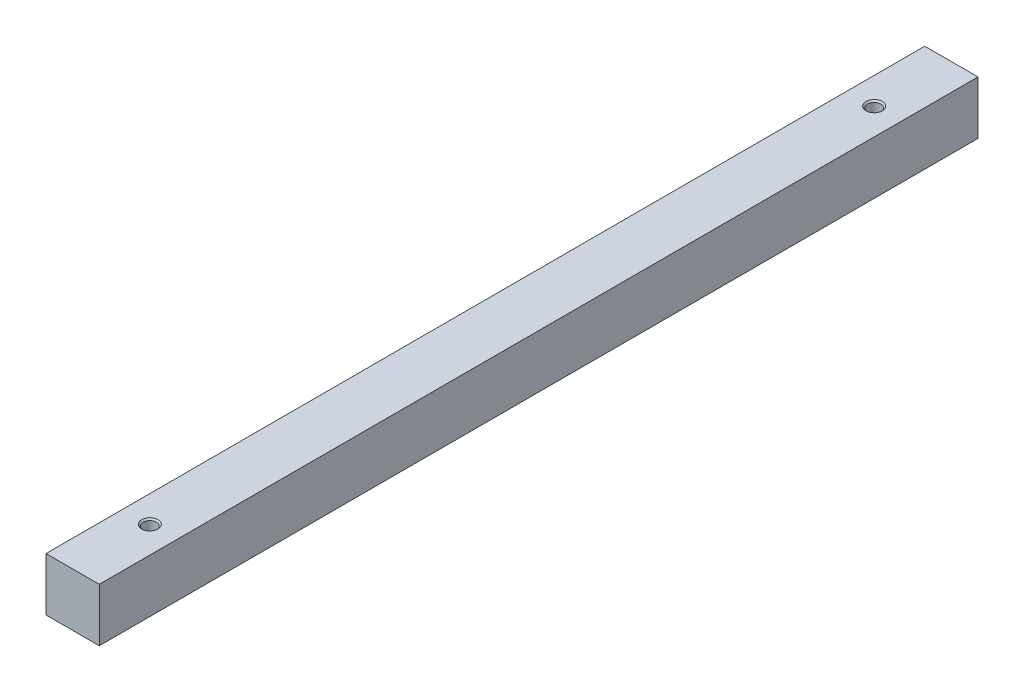
SolidWorks part; units mm, degrees
ref_plane "Plan de face" through (0, 0, 0) normal (0, 0, 1) x (1, 0, 0)
ref_plane "Plan de dessus" through (0, 0, 0) normal (0, 1, 0) x (1, 0, 0)
ref_plane "Plan de droite" through (0, 0, 0) normal (1, 0, 0) x (0, 0, -1)
sketch "Esquisse1" plane through (0, 0, 0) normal (0, 0, 1) x (1, 0, 0)
  line L0 (-5, 5) -> (5, -5) construction
  line L1 (-5, 5) -> (5, 5)
  line L2 (-5, 5) -> (-5, -5)
  line L3 (-5, -5) -> (5, -5)
  line L4 (5, 5) -> (5, -5)
  dimension "D1" = 10
extrude "Boss.-Extru.1" add sketch "Esquisse1" along normal mid plane 165
hole_wizard "Trou taraudé M3x0.52" positions "Esquisse5" profile "Esquisse4" tap size "M3x0.5" standard "Ansi Metric" end condition through all
sketch "Esquisse5" plane through (0, 5, 0) normal (0, 1, 0) x (1, 0, 0)
  line L0 (0, 0) -> (-36.1539, 0) construction
  line L2 (5, 82.5) -> (-5, 82.5) construction
  point P0 (0, 68)
  point P2 (0, -68)
  dimension "D1" = 68
  dimension "D2" = 14.5
sketch "Esquisse4" plane through (0, 5, -68) normal (1, 0, 0) x (0, 0, 1)
  line L0 (0, 0) -> (0, 10)
  line L1 (0, 10) -> (1.25, 10)
  line L2 (1.25, 10) -> (1.25, 0.275)
  line L3 (1.25, 0.275) -> (1.525, 0)
  line L5 (1.525, 0) -> (0, 0)
  line L6 (-1.25, 0.275) -> (-1.525, 0) construction
  line L11 (0, -6.35) -> (0, 107.95) construction
  dimension "Diamètre du trou pour taraudage jusqu'au prochain" = 2.5
  dimension "Profondeur du trou pour taraudage jusqu'au prochain" = 10
  dimension "Diamètre du fraisage entrant" = 3.05
  dimension "Angle du fraisage entrant" = 90
cosmetic thread "Filetage de perçage3"
cosmetic thread "Filetage de perçage4"
